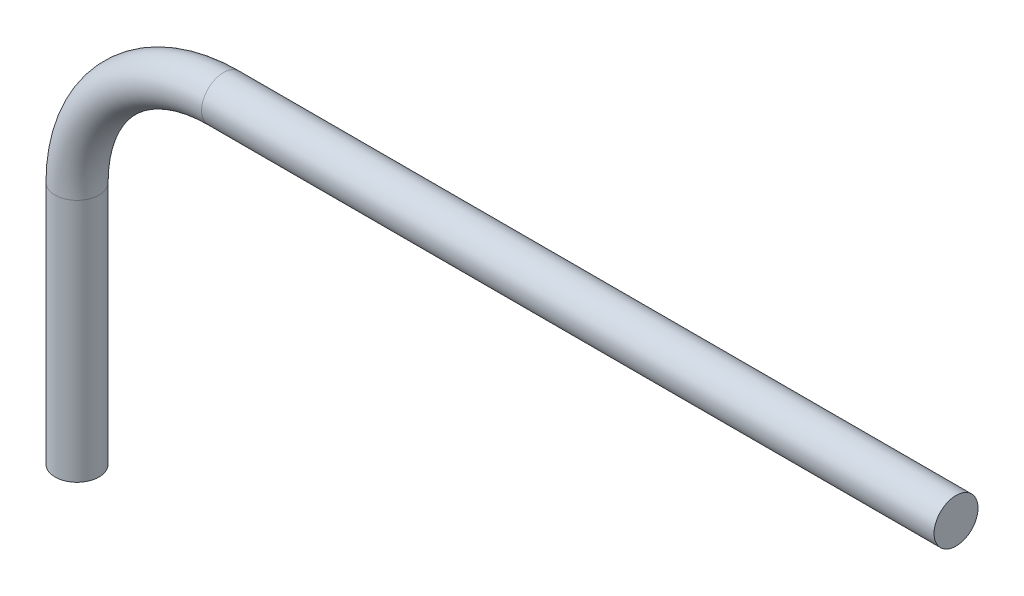
SolidWorks part; units mm, degrees
ref_plane "Front Plane" through (0, 0, 0) normal (0, 0, 1) x (1, 0, 0)
ref_plane "Top Plane" through (0, 0, 0) normal (0, 1, 0) x (1, 0, 0)
ref_plane "Right Plane" through (0, 0, 0) normal (1, 0, 0) x (0, 0, -1)
sketch "Sketch1" plane through (0, 0, 0) normal (0, 1, 0) x (1, 0, 0)
  circle A0 centre (0, 0) radius 4.5
  dimension "D1" = 9
sketch "Sketch2" plane through (0, 0, 0) normal (0, 0, 1) x (1, 0, 0)
  line L0 (0, 0) -> (0, 50)
  line L1 (30, 80) -> (180, 80)
  arc A0 (0, 50) -> (30, 80) centre (30, 50) cw
  point P6 (0, 80)
  dimension "D3" = 30
  dimension "D1" = 180
  dimension "D2" = 80
sweep "Sweep1" add profiles "Sketch1" path "Sketch2"
